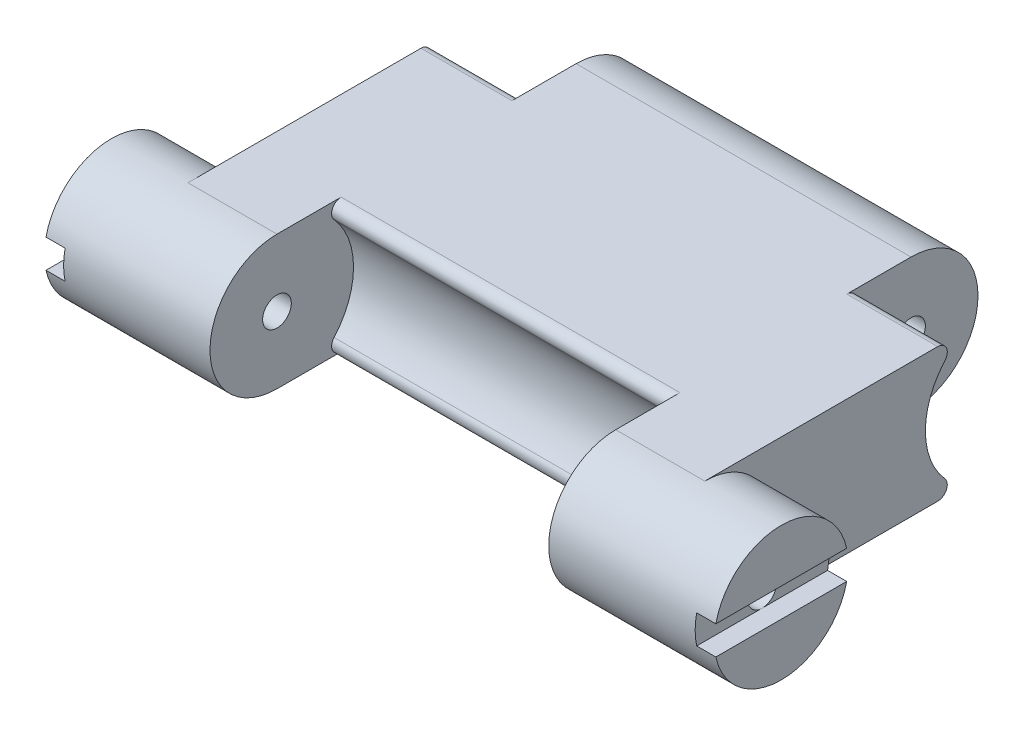
SolidWorks part; units mm, degrees
ref_plane "Спереди" through (0, 0, 0) normal (0, 0, 1) x (1, 0, 0)
ref_plane "Сверху" through (0, 0, 0) normal (0, 1, 0) x (1, 0, 0)
ref_plane "Справа" through (0, 0, 0) normal (1, 0, 0) x (0, 0, -1)
sketch "Эскиз1" plane through (0, 0, 0) normal (1, 0, 0) x (0, 0, -1)
  line L0 (-7.765, 3.5) -> (7.765, 3.5) construction
  line L1 (-7.765, 7) -> (7.765, 7)
  line L2 (-7.765, 0) -> (7.765, 0)
  arc A0 (-7.765, 7) -> (-7.765, 0) centre (-7.765, 3.5) ccw
  arc A1 (7.765, 0) -> (7.765, 7) centre (7.765, 3.5) ccw
  point P2 (0, 3.5)
  dimension "D1" = 15.53
  dimension "D2" = 7
extrude "Бобышка-Вытянуть1" add sketch "Эскиз1" along normal mid plane 35
sketch "Эскиз3" plane through (17.5, 0, 0) normal (1, 0, 0) x (0, 0, -1)
  line L0 (7.765, 7) -> (-7.765, 7) construction
  line L1 (-12, 8) -> (12, 8)
  line L2 (-12, 8) -> (-12, -1)
  line L3 (-12, -1) -> (12, -1)
  line L4 (12, 8) -> (12, -1)
  line L5 (-12, 8) -> (12, -1) construction
  line L6 (-12, -1) -> (12, 8) construction
  line L7 (-7.765, 0) -> (7.765, 0) construction
  circle A0 centre (-7.765, 3.5) radius 3.5
  arc A1 (-7.765, 7) -> (-7.765, 0) centre (-7.765, 3.5) ccw construction
  point P9 (0, 3.5)
  dimension "D1" = 1
  dimension "D2" = 1
  dimension "D3" = 12
  dimension "D4" = 24
extrude "Вырез-Вытянуть1" cut sketch "Эскиз3" against normal blind 4
mirror "Зеркальное отражение1" about plane through (0, 0, 0) normal (1, 0, 0) of "Вырез-Вытянуть1"
sketch "Эскиз6" plane through (0, 0, 0) normal (1, 0, 0) x (0, 0, -1)
  circle A0 centre (-7.765, 3.5) radius 4
  circle A1 centre (-7.765, 3.5) radius 3.5 construction
  dimension "D1" = 8
extrude "Вырез-Вытянуть2" cut sketch "Эскиз6" against normal mid plane 17.7
sketch "Эскиз7" plane through (13.5, 0, 0) normal (1, 0, 0) x (0, 0, -1)
  circle A0 centre (7.765, 3.5) radius 4
  arc A1 (7.765, 0) -> (7.765, 7) centre (7.765, 3.5) ccw construction
  dimension "D2" = 8
  dimension "D1" = 0
extrude "Вырез-Вытянуть3" cut sketch "Эскиз7" against normal blind 4.75
sketch "Эскиз9" plane through (17.5, 0, 0) normal (1, 0, 0) x (0, 0, -1)
  line L1 (-11.365, 2.75) -> (-4.165, 2.75)
  line L2 (-11.365, 2.75) -> (-11.365, 4.25)
  line L3 (-11.365, 4.25) -> (-4.165, 4.25)
  line L4 (-4.165, 2.75) -> (-4.165, 4.25)
  line L5 (-11.365, 2.75) -> (-4.165, 4.25) construction
  line L6 (-11.365, 4.25) -> (-4.165, 2.75) construction
  circle A0 centre (-7.765, 3.5) radius 3.5 construction
  circle A1 centre (-7.765, 3.5) radius 3.5 construction
  point P4 (-7.765, 3.5)
  point P8 (-7.765, 3.5)
  dimension "D1" = 1.5
  dimension "D2" = 7.2
extrude "Вырез-Вытянуть5" cut sketch "Эскиз9" against normal blind 1
mirror "Зеркальное отражение2" about plane through (0, 0, 0) normal (1, 0, 0) of "Вырез-Вытянуть5", "Вырез-Вытянуть3"
fillet "Скругление1" radius 0.5 6 edges at (-11.125, 0, -5.8285) (-11.125, 7, -5.8285) (0, 7, 5.8285) (0, 0, 5.8285) (11.125, 7, -5.8285) (11.125, 0, -5.8285)
sketch "Эскиз8" plane through (17.5, 0, 0) normal (1, 0, 0) x (0, 0, -1)
  circle A0 centre (-7.765, 3.5) radius 0.75
  circle A1 centre (7.765, 3.5) radius 0.75
  arc A2 (7.765, 0) -> (7.765, 7) centre (7.765, 3.5) ccw construction
  circle A3 centre (-7.765, 3.5) radius 3.5 construction
  point P4 (0, 0)
  dimension "D1" = 1.5
extrude "Вырез-Вытянуть4" cut sketch "Эскиз8" against normal through all
ref_plane "Плоскость4" through (-15.5, 0, 0) normal (-1, 0, 0) x (0, 0, 1)
